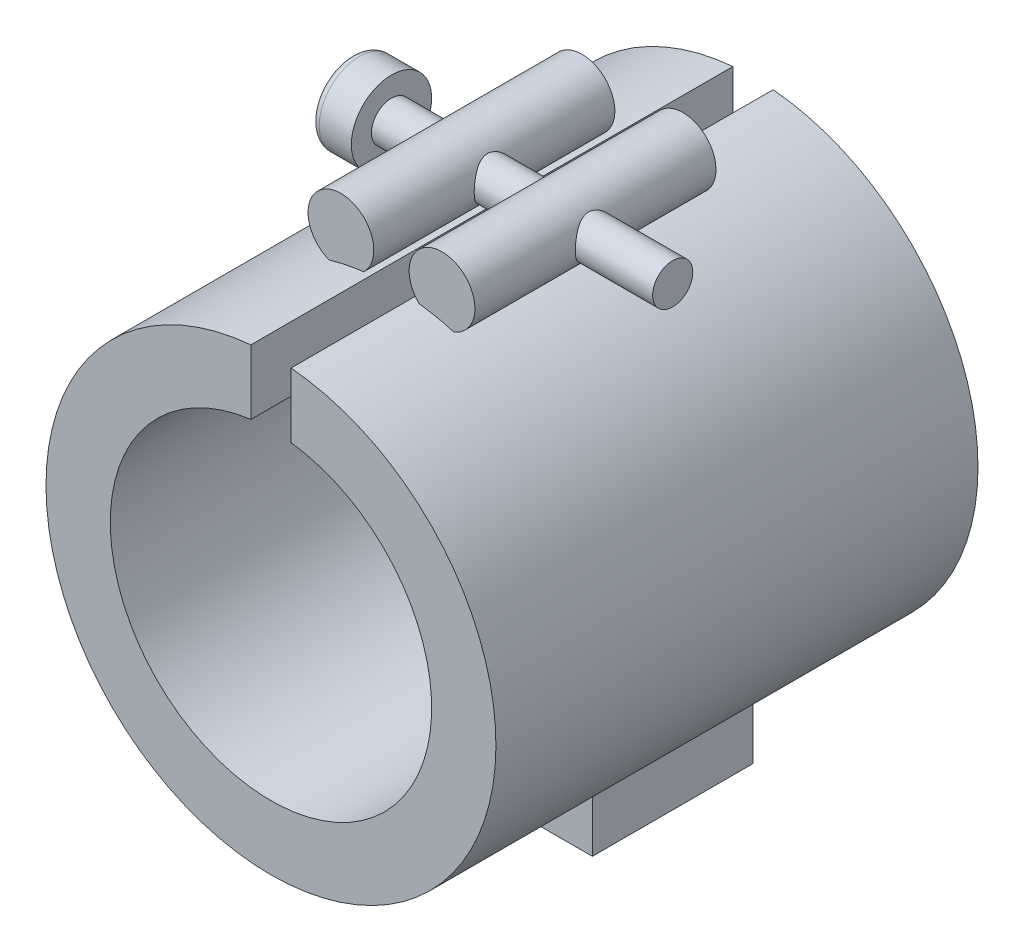
SolidWorks part; units mm, degrees
ref_plane "Front Plane" through (0, 0, 0) normal (0, 0, 1) x (1, 0, 0)
ref_plane "Top Plane" through (0, 0, 0) normal (0, 1, 0) x (1, 0, 0)
ref_plane "Right Plane" through (0, 0, 0) normal (1, 0, 0) x (0, 0, -1)
sketch "Sketch1" plane through (0, 0, 0) normal (0, 0, 1) x (1, 0, 0)
  line L0 (-2.5, 27.8882) -> (-2.5, 19.8431)
  line L1 (0, 0) -> (0, 34.2254) construction
  line L2 (2.5, 27.8882) -> (2.5, 19.8431)
  arc A0 (-2.5, 27.8882) -> (2.5, 27.8882) centre (0, 0) ccw
  arc A1 (-2.5, 19.8431) -> (2.5, 19.8431) centre (0, 0) ccw
  dimension "D1" = 40
  dimension "D2" = 8
  dimension "D3" = 5
extrude "Boss-Extrude1" add sketch "Sketch1" along normal mid plane 60
sketch "Sketch2" plane through (0, 0, 0) normal (0, 0, 1) x (1, 0, 0)
  line L0 (0, 0) -> (0, 40.0287) construction
  circle A0 centre (6.2935, 30.7225) radius 4.0912
  circle A1 centre (-6.2935, 30.7225) radius 4.0912
  arc A2 (-2.5, 27.8882) -> (2.5, 27.8882) centre (0, 0) ccw construction
  arc A3 (-2.5, 27.8882) -> (2.5, 27.8882) centre (0, 0) ccw construction
  dimension "D1" = 2.8343
  dimension "D3" = 8.1825
  dimension "D2" = 12.5871
extrude "Boss-Extrude2" add sketch "Sketch2" along normal mid plane 30
sketch "Sketch3" plane through (0, 0, 0) normal (0, 0, 1) x (1, 0, 0)
  line L0 (0, 0) -> (0, -23.0171) construction
  line L1 (-10, -23.0171) -> (10, -23.0171)
  line L2 (-10, -23.0171) -> (-10, -36)
  line L3 (-10, -36) -> (10, -36)
  line L4 (10, -23.0171) -> (10, -36)
  arc A0 (-2.5, 27.8882) -> (2.5, 27.8882) centre (0, 0) ccw construction
  dimension "D2" = 36
  dimension "D1" = 20
extrude "Boss-Extrude3" add sketch "Sketch3" against normal blind 20
sketch "Sketch4" plane through (0, 0, 0) normal (0, 0, 1) x (1, 0, 0)
  circle A0 centre (0, -38.1274) radius 3.5547
sketch "Sketch5" plane through (0, 0, 0) normal (1, 0, 0) x (0, 0, -1)
  circle A0 centre (0, 30.7225) radius 2.5
  dimension "D1" = 5
extrude "Boss-Extrude5" add sketch "Sketch5" along normal blind 20 and the other way blind 20
sketch "Sketch6" plane through (-20, 0, 0) normal (-1, 0, 0) x (0, 0, 1)
  circle A0 centre (0, 30.7225) radius 5
  circle A1 centre (0, 30.7225) radius 2.5 construction
  dimension "D1" = 10
extrude "Boss-Extrude6" add sketch "Sketch6" against normal blind 5
sketch "Sketch7" plane through (-20, 0, 0) normal (-1, 0, 0) x (0, 0, 1)
  line L1 (1.5877, 27.9725) -> (3.1754, 30.7225)
  line L2 (3.1754, 30.7225) -> (1.5877, 33.4725)
  line L3 (1.5877, 33.4725) -> (-1.5877, 33.4725)
  line L4 (-1.5877, 33.4725) -> (-3.1754, 30.7225)
  line L5 (-3.1754, 30.7225) -> (-1.5877, 27.9725)
  line L6 (-1.5877, 27.9725) -> (1.5877, 27.9725)
  circle A0 centre (0, 30.7225) radius 2.75 construction
  circle A1 centre (0, 30.7225) radius 5 construction
  point P10 (0, 27.9725)
  dimension "D1" = 5.5
extrude "Cut-Extrude1" cut sketch "Sketch7" against normal blind 3
fillet "Fillet2" radius 1 1 edges at (-20, 30.7225, 5)
